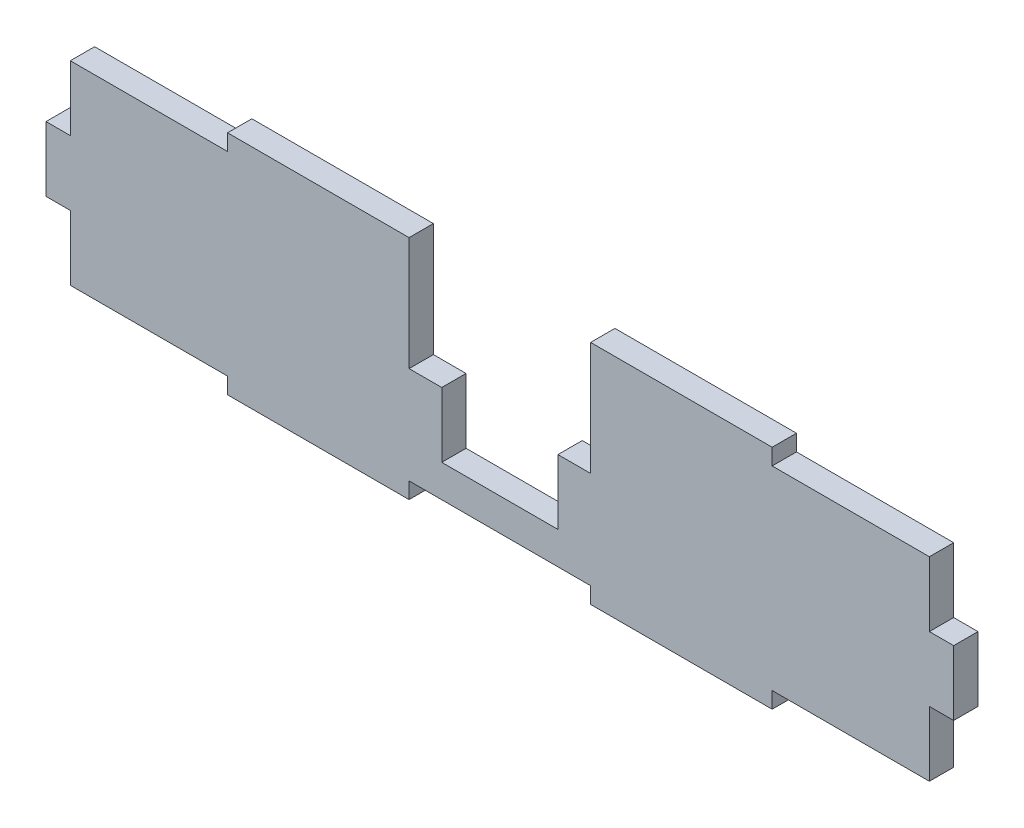
SolidWorks part; units mm, degrees
ref_plane "Front" through (0, 0, 0) normal (0, 0, 1) x (1, 0, 0)
ref_plane "Top" through (0, 0, 0) normal (0, 1, 0) x (1, 0, 0)
ref_plane "Right" through (0, 0, 0) normal (1, 0, 0) x (0, 0, -1)
sketch "Sketch1" plane through (0, 0, 0) normal (0, 0, 1) x (1, 0, 0)
  line L5 (216.9413, 43.982) -> (-138.6587, 43.982)
  line L6 (216.9413, 43.982) -> (216.9413, -32.218)
  line L7 (216.9413, -32.218) -> (-138.6587, -32.218)
  line L8 (-138.6587, -32.218) -> (-138.6587, 43.982)
  line L9 (216.9413, 5.882) -> (-138.6587, 5.882) construction
  line L10 (39.1413, 43.982) -> (39.1413, -32.218) construction
  line L11 (-67.5387, -32.218) -> (-67.5387, -38.568)
  line L12 (-67.5387, -38.568) -> (3.5813, -38.568)
  line L13 (3.5813, -38.568) -> (3.5813, -32.218)
  line L14 (3.5813, -32.218) -> (-67.5387, -32.218)
  line L15 (74.7013, -38.568) -> (74.7013, -32.218)
  line L16 (145.8213, -38.568) -> (74.7013, -38.568)
  line L17 (145.8213, -32.218) -> (145.8213, -38.568)
  line L18 (74.7013, -32.218) -> (145.8213, -32.218)
  line L19 (-138.6587, 18.582) -> (-129.1337, 18.582)
  line L20 (-129.1337, 18.582) -> (-129.1337, 43.982)
  line L21 (-138.6587, 43.982) -> (-129.1337, 43.982)
  line L22 (-138.6587, 43.982) -> (-138.6587, 18.582)
  line L23 (-138.6587, -32.218) -> (-129.1337, -32.218)
  line L24 (-129.1337, -6.818) -> (-129.1337, -32.218)
  line L25 (-138.6587, -6.818) -> (-129.1337, -6.818)
  line L26 (-138.6587, -32.218) -> (-138.6587, -6.818)
  line L27 (216.9413, -32.218) -> (216.9413, -6.818)
  line L28 (216.9413, -6.818) -> (207.4163, -6.818)
  line L29 (207.4163, -6.818) -> (207.4163, -32.218)
  line L30 (216.9413, -32.218) -> (207.4163, -32.218)
  line L31 (216.9413, 43.982) -> (207.4163, 43.982)
  line L32 (207.4163, 18.582) -> (207.4163, 43.982)
  line L33 (216.9413, 18.582) -> (207.4163, 18.582)
  line L34 (216.9413, 43.982) -> (216.9413, 18.582)
  line L35 (145.8213, 50.332) -> (74.7013, 50.332)
  line L36 (145.8213, 43.982) -> (145.8213, 50.332)
  line L37 (74.7013, 43.982) -> (145.8213, 43.982)
  line L38 (74.7013, 50.332) -> (74.7013, 43.982)
  line L39 (3.5813, 50.332) -> (3.5813, 43.982)
  line L40 (-67.5387, 50.332) -> (3.5813, 50.332)
  line L41 (-67.5387, 43.982) -> (-67.5387, 50.332)
  line L42 (3.5813, 43.982) -> (-67.5387, 43.982)
  line L43 (3.5813, 43.982) -> (3.5813, 20.7751)
  line L44 (3.5813, 43.982) -> (3.5813, 5.882)
  line L45 (3.5813, 5.882) -> (74.7013, 5.882)
  line L46 (74.7013, 5.882) -> (74.7013, 43.982)
  line L47 (16.3826, 5.882) -> (16.3826, -19.518)
  line L48 (61.9, 5.882) -> (61.9, -19.518)
  line L49 (61.9, -19.518) -> (14.3624, -19.518)
  line L50 (16.3826, 5.882) -> (61.9, 5.882)
  dimension "D1" = 355.6
  dimension "D2" = 76.2
  dimension "D3" = 71.12
  dimension "D4" = 71.12
  dimension "D5" = 6.35
  dimension "D6" = 9.525
  dimension "D7" = 25.4
  dimension "D8" = 38.1
extrude "Boss-Extrude1" add sketch "Sketch1" along normal blind 9.525 contours L8 L7 L6 L5 | L17 L7 L15 L16 | L12 L13 L7 L11 | L39 L42 L41 L40 | L35 L38 L37 L36
